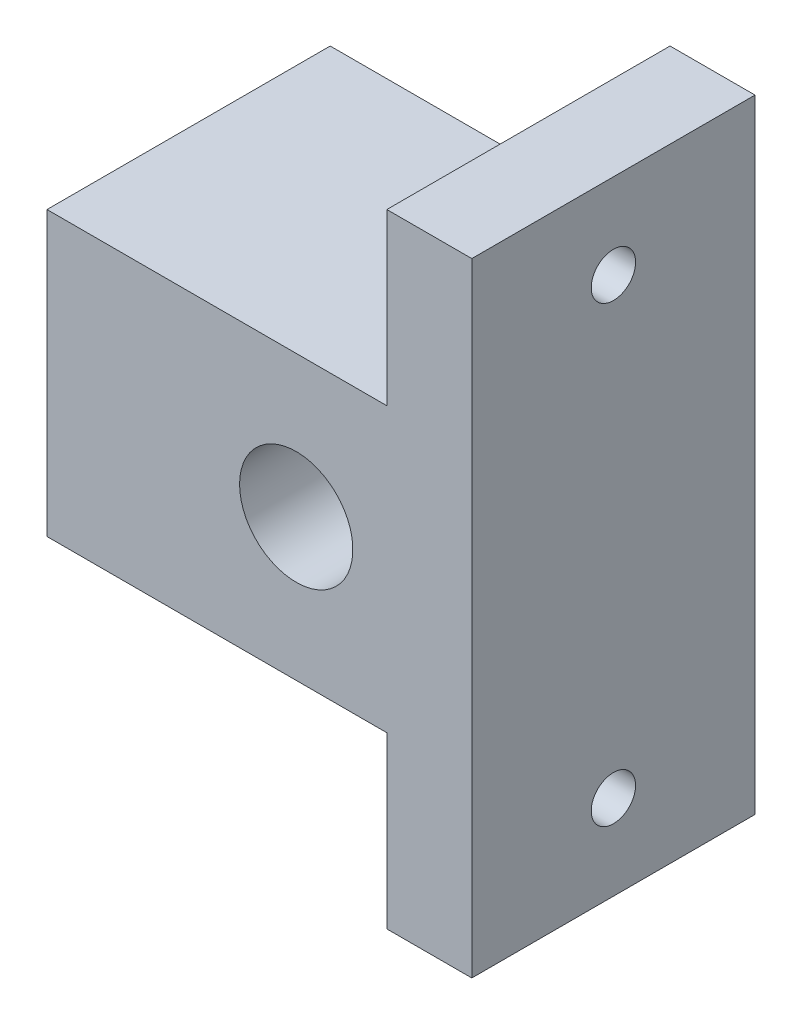
SolidWorks part; units mm, degrees
ref_plane "Front Plane" through (0, 0, 0) normal (0, 0, 1) x (1, 0, 0)
ref_plane "Top Plane" through (0, 0, 0) normal (0, 1, 0) x (1, 0, 0)
ref_plane "Right Plane" through (0, 0, 0) normal (1, 0, 0) x (0, 0, -1)
ref_plane "Plane1" through (0, 0, 15) normal (0, 0, -1) x (-1, 0, 0)
sketch "Sketch1" plane through (0, 0, 15) normal (0, 0, -1) x (-1, 0, 0)
  line L0 (47.5, -11) -> (47.5, 11)
  line L1 (47.5, 11) -> (32.5, 11)
  line L2 (32.5, 11) -> (32.5, -11)
  line L3 (32.5, -11) -> (47.5, -11)
extrude "Boss-Extrude1" add sketch "Sketch1" against normal blind 10
sketch "Sketch2" plane through (0, 0, 25) normal (0, 0, 1) x (1, 0, 0)
  line L0 (-47.5, 5) -> (-35.5, 5)
  line L1 (-35.5, 5) -> (-35.5, 11)
  line L2 (-35.5, 11) -> (-47.5, 11)
  line L3 (-47.5, 11) -> (-47.5, 5)
extrude "Cut-Extrude1" cut sketch "Sketch2" against normal through all
sketch "Sketch3" plane through (0, 0, 25) normal (0, 0, 1) x (1, 0, 0)
  line L0 (-35.5, -11) -> (-35.5, -5)
  line L1 (-35.5, -5) -> (-47.5, -5)
  line L2 (-47.5, -5) -> (-47.5, -11)
  line L3 (-47.5, -11) -> (-35.5, -11)
extrude "Cut-Extrude2" cut sketch "Sketch3" against normal through all
ref_plane "Plane2" through (0, 0, 20) normal (0, 0, 1) x (1, 0, 0)
sketch "Sketch4" plane through (0, 0, 20) normal (0, 0, 1) x (1, 0, 0)
  line L0 (-35.5, 8.7835) -> (-35.5, 8)
  line L1 (-35.5, 8) -> (-32.5, 8)
  line L2 (-32.5, 8) -> (-32.5, 8.7835)
  line L3 (-32.5, 8.7835) -> (-34.5, 8.7835)
  line L4 (-34.5, 8.7835) -> (-35.5, 8.7835)
  line L5 (-35.5, 8) -> (-32.5, 8) construction
revolve "Cut-Revolve1" cut sketch "Sketch4" angle 360 about L5
sketch "Sketch5" plane through (0, 0, 20) normal (0, 0, 1) x (1, 0, 0)
  line L0 (-35.5, -7.2165) -> (-35.5, -8)
  line L1 (-35.5, -8) -> (-32.5, -8)
  line L2 (-32.5, -8) -> (-32.5, -7.2165)
  line L3 (-32.5, -7.2165) -> (-34.5, -7.2165)
  line L4 (-34.5, -7.2165) -> (-35.5, -7.2165)
  line L5 (-35.5, -8) -> (-32.5, -8) construction
revolve "Cut-Revolve2" cut sketch "Sketch5" angle 360 about L5
hole_wizard "Ø4.0 (4) Diameter Hole1" positions "Sketch7" profile "Sketch6" hole size "Ø4.0" standard "ANSI Metric"
sketch "Sketch7" plane through (0, 0, 15) normal (0, 0, -1) x (-1, 0, 0)
  point P0 (38.7, 0)
sketch "Sketch6" plane through (-38.7, 0, 15) normal (1, 0, 0) x (0, 1, 0)
  line L0 (0, 0) -> (0, 10)
  line L1 (0, 10) -> (2, 10)
  line L2 (2, 10) -> (2, 0)
  line L5 (2, 0) -> (0, 0)
  line L11 (0, -6.35) -> (0, 107.95) construction
  dimension "Thru Hole Dia." = 4
  dimension "Thru Hole Depth" = 10
